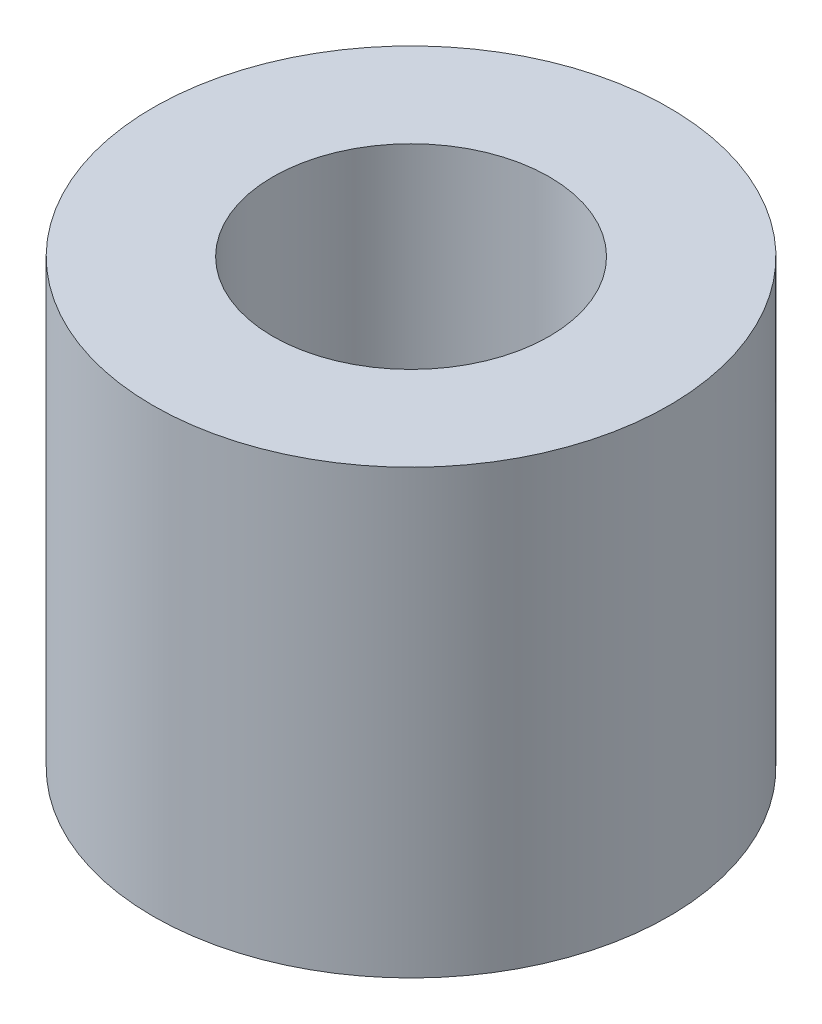
SolidWorks part; units mm, degrees
ref_plane "Front" through (0, 0, 0) normal (0, 0, 1) x (1, 0, 0)
ref_plane "Top" through (0, 0, 0) normal (0, 1, 0) x (1, 0, 0)
ref_plane "Right" through (0, 0, 0) normal (1, 0, 0) x (0, 0, -1)
sketch "Croquis1" plane through (0, 0, 0) normal (0, 1, 0) x (1, 0, 0)
  circle A0 centre (0, 0) radius 3.5
  circle A1 centre (0, 0) radius 1.875
  dimension "D1" = 7
  dimension "D2" = 3.75
extrude "Saliente-Extruir1" add sketch "Croquis1" along normal blind 6
